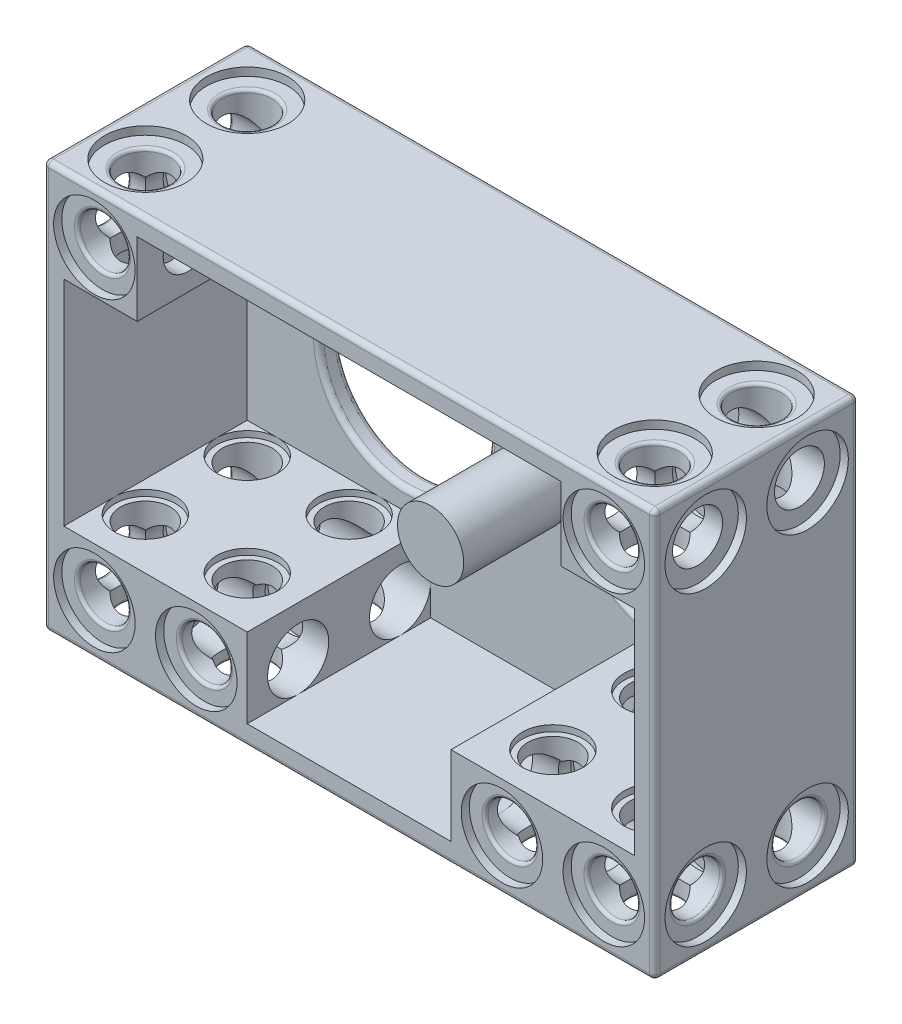
SolidWorks part; units mm, degrees
ref_plane "Front Plane" through (0, 0, 0) normal (0, 0, 1) x (1, 0, 0)
ref_plane "Top Plane" through (0, 0, 0) normal (0, 1, 0) x (1, 0, 0)
ref_plane "Right Plane" through (0, 0, 0) normal (1, 0, 0) x (0, 0, -1)
sketch "Sketch1" plane through (0, 0, 0) normal (0, 0, 1) x (1, 0, 0)
  line L0 (0, 20) -> (0, -20) construction
  line L1 (-30, -20) -> (30, -20)
  line L2 (-30, -20) -> (-30, 20)
  line L3 (-30, 20) -> (30, 20)
  line L4 (30, -20) -> (30, 20)
  line L5 (-30, -20) -> (30, 20) construction
  line L6 (-30, 20) -> (30, -20) construction
  line L7 (-23, 10.8) -> (23, 10.8)
  line L8 (-23, 10.8) -> (-23, -10.2)
  line L9 (-23, -10.2) -> (23, -10.2)
  line L10 (23, 10.8) -> (23, -10.2)
  line L11 (-12.6, 0.2) -> (12.6, 0.2) construction
  line L12 (-30, 12.5) -> (30, 12.5) construction
  line L13 (-30, -12.5) -> (30, -12.5) construction
  line L14 (30, -12.5) -> (35.4967, -17.0033) construction
  line L15 (-30, -2.5) -> (30, -2.5) construction
  line L16 (-20, 20) -> (-20, -20) construction
  line L17 (20, 20) -> (20, -20) construction
  line L18 (-30, 2.5) -> (30, 2.5) construction
  circle A0 centre (-12.6, 0.2) radius 8.4
  circle A1 centre (12.6, 0.2) radius 8.4
  point P0 (0, 0)
  point P12 (0, -10.2)
  point P17 (0, 0.2)
  point P31 (0, 0)
  dimension "D5" = 16.8
  dimension "D1" = 40
  dimension "D2" = 60
  dimension "D3" = 46
  dimension "D4" = 21
  dimension "D6" = 25.2
  dimension "D7" = 10.6
  dimension "D8" = 7.5
  dimension "D9" = 7.5
  dimension "D10" = 10
  dimension "D11" = 10
  dimension "D12" = 10
  dimension "D13" = 10
  dimension "D14" = 9.2
extrude "Boss-Extrude1" add sketch "Sketch1" along normal blind 2 contours L1 L4 L3 L2 L7 L10 L9 L8 | L10 L7 L8 L9 A1 A0
sketch "Sketch2" plane through (0, 0, 2) normal (0, 0, 1) x (1, 0, 0)
  line L0 (0, 20) -> (0, -20) construction
  line L1 (-23, 10.8) -> (23, 10.8) construction
  circle A0 centre (0, -1.7) radius 3.25
  dimension "D1" = 6.5
  dimension "D2" = 12.5
extrude "Boss-Extrude2" add sketch "Sketch2" along normal blind 10
sketch "Sketch3" plane through (0, 0, 2) normal (0, 0, 1) x (1, 0, 0)
  line L0 (-30, -20) -> (30, -20) construction
  line L1 (30, -20) -> (30, 20) construction
  line L2 (-30, 20) -> (30, 20) construction
  line L3 (-30, -20) -> (-30, 20) construction
  line L4 (-30, -20) -> (30, -20)
  line L5 (30, -20) -> (30, 20)
  line L6 (-30, 20) -> (30, 20)
  line L7 (-30, -20) -> (-30, 20)
  line L8 (-28, -18) -> (28, -18)
  line L9 (28, -18) -> (28, 18)
  line L10 (-28, 18) -> (28, 18)
  line L11 (-28, -18) -> (-28, 18)
  dimension "D1" = 2
extrude "Boss-Extrude4" add sketch "Sketch3" along normal offset from surface (18 mm away) 20 up to face at (0, 0, 0)
sketch "Sketch5" plane through (0, 0, 2) normal (0, 0, 1) x (1, 0, 0)
  line L0 (-23, 10.8) -> (23, 10.8) construction
  line L1 (-30, 20) -> (-20.8, 20)
  line L2 (-30, 20) -> (-30, 10.8)
  line L3 (-30, 10.8) -> (-20.8, 10.8)
  line L4 (-20.8, 20) -> (-20.8, 10.8)
  line L6 (30, 20) -> (20.8, 20)
  line L7 (30, 20) -> (30, 10.8)
  line L8 (30, 10.8) -> (20.8, 10.8)
  line L9 (20.8, 20) -> (20.8, 10.8)
  line L11 (30, -20) -> (20.8, -20)
  line L12 (30, -20) -> (30, -10.2)
  line L13 (30, -10.2) -> (20.8, -10.2)
  line L14 (20.8, -20) -> (20.8, -10.2)
  line L15 (-30, -20) -> (-20.8, -20)
  line L16 (-30, -20) -> (-30, -10.2)
  line L17 (-30, -10.2) -> (-20.8, -10.2)
  line L18 (-20.8, -20) -> (-20.8, -10.2)
  line L19 (-23, -10.2) -> (23, -10.2) construction
  point P23 (0, 0)
  point P24 (0, 0)
  dimension "D1" = 9.2
extrude "Boss-Extrude5" add sketch "Sketch5" along normal up to surface (18 mm away) up to face at (0, 0, 20)
sketch "Sketch7" plane through (0, 0, 2) normal (0, 0, 1) x (1, 0, 0)
  line L1 (-30, 20) -> (-21, 20)
  line L2 (-30, 20) -> (-30, 10.8)
  line L3 (-30, 10.8) -> (-21, 10.8)
  line L4 (-21, 20) -> (-21, 10.8)
  line L5 (30, 20) -> (21, 20)
  line L6 (30, 20) -> (30, 10.8)
  line L7 (30, 10.8) -> (21, 10.8)
  line L8 (21, 20) -> (21, 10.8)
  dimension "D1" = 9
  dimension "D2" = 9.2
  dimension "D3" = 9.2
  dimension "D4" = 9
extrude "Boss-Extrude6" add sketch "Sketch7" along normal up to surface (18 mm away)
sketch "Sketch8" plane through (0, 0, 2) normal (0, 0, 1) x (1, 0, 0)
  line L0 (30, -20) -> (30, 20) construction
  line L1 (-30, -20) -> (30, -20)
  line L2 (-30, -20) -> (-30, -10.2)
  line L3 (-30, -10.2) -> (30, -10.2)
  line L4 (30, -20) -> (30, -10.2)
  line L5 (0, 20) -> (0, -20) construction
  line L6 (-6, -20) -> (6, -20)
  line L7 (-6, -20) -> (-6, -10.2)
  line L8 (-6, -10.2) -> (6, -10.2)
  line L9 (6, -20) -> (6, -10.2)
  line L10 (-20.8, -10.2) -> (-28, -10.2) construction
  line L11 (-30, -20) -> (-10, -20)
  line L12 (-30, -20) -> (-30, -10.2)
  line L13 (-30, -10.2) -> (-10, -10.2)
  line L14 (-10, -20) -> (-10, -10.2)
  line L15 (30, -20) -> (10, -20)
  line L16 (30, -20) -> (30, -10.2)
  line L17 (30, -10.2) -> (10, -10.2)
  line L18 (10, -20) -> (10, -10.2)
  point P19 (0, 0)
  line M24 (-20.8, -10.2) -> (-20.8, -18)
  line M25 (-20.8, -18) -> (20.8, -18)
  line M26 (20.8, -18) -> (20.8, -10.2)
  dimension "D2" = 12
  dimension "D3" = 6
  dimension "D4" = 20
  dimension "D5" = 20
extrude "Boss-Extrude7" add sketch "Sketch8" along normal up to surface (18 mm away) contours L14 L3 M25 M24 | L18 L3 M25 M26
sketch "Sketch9" plane through (-30, 0, 0) normal (-1, 0, 0) x (0, 0, 1)
  line L0 (0, 15) -> (20, 15) construction
  line L1 (0, -20) -> (0, 20) construction
  line L2 (20, 20) -> (20, -20) construction
  line L3 (20, 20) -> (0, 20) construction
  line L4 (0, 0) -> (20, 0) construction
  circle A0 centre (5, 15) radius 2.45
  circle A1 centre (15, 15) radius 2.45
  circle A2 centre (5, -15) radius 2.45
  circle A3 centre (15, -15) radius 2.45
  dimension "D1" = 5
  dimension "D2" = 4.9
  dimension "D3" = 5
  dimension "D4" = 10
extrude "Cut-Extrude1" cut sketch "Sketch9" against normal through all
sketch "Sketch10" plane through (0, 20, 0) normal (0, 1, 0) x (1, 0, 0)
  line L0 (-25, 0) -> (-25, -20) construction
  line L1 (-30, 0) -> (30, 0) construction
  line L2 (30, -20) -> (-30, -20) construction
  line L3 (-30, -20) -> (-30, 0) construction
  line L4 (0, 0) -> (0, -20) construction
  circle A0 centre (-25, -5) radius 2.45
  circle A1 centre (-25, -15) radius 2.45
  circle A2 centre (25, -15) radius 2.45
  circle A3 centre (25, -5) radius 2.45
  dimension "D1" = 5
  dimension "D2" = 4.9
  dimension "D3" = 5
  dimension "D4" = 10
extrude "Cut-Extrude2" cut sketch "Sketch10" against normal through all
sketch "Sketch11" plane through (0, -20, 0) normal (0, -1, 0) x (1, 0, 0)
  line L0 (-15, 20) -> (-15, 0) construction
  line L1 (-30, 20) -> (30, 20) construction
  line L2 (-30, 0) -> (30, 0) construction
  line L3 (0, 0) -> (0, 20) construction
  circle A0 centre (-15, 15) radius 2.45
  circle A1 centre (-15, 5) radius 2.45
  circle A2 centre (-25, 15) radius 2.45 construction
  circle A3 centre (15, 15) radius 2.45
  circle A4 centre (15, 5) radius 2.45
  dimension "D1" = 10
  dimension "D2" = 4.9
  dimension "D3" = 5
  dimension "D4" = 10
extrude "Cut-Extrude3" cut sketch "Sketch11" against normal blind 13
sketch "Sketch12" plane through (0, 0, 20) normal (0, 0, 1) x (1, 0, 0)
  line L0 (-30, -15) -> (30, -15) construction
  line L1 (-30, 20) -> (-30, -20) construction
  line L2 (30, -20) -> (30, 20) construction
  line L3 (0, 0) -> (18.5352, 0) construction
  line L4 (0, -20) -> (0, 0) construction
  line L5 (-30, -20) -> (30, -20) construction
  circle A0 centre (-25, -15) radius 2.45
  circle A1 centre (-15, -15) radius 2.45
  circle A2 centre (15, -15) radius 2.45
  circle A3 centre (25, -15) radius 2.45
  circle A4 centre (25, 15) radius 2.45
  circle A5 centre (-25, 15) radius 2.45
  dimension "D1" = 5
  dimension "D2" = 4.9
  dimension "D3" = 5
  dimension "D4" = 10
extrude "Cut-Extrude4" cut sketch "Sketch12" against normal blind 10
sketch "Sketch13" plane through (0, 20, 0) normal (0, 1, 0) x (1, 0, 0)
  circle A0 centre (-25, -5) radius 4
  circle A1 centre (-25, -15) radius 4
  circle A2 centre (25, -5) radius 4
  circle A3 centre (25, -15) radius 4
  dimension "D1" = 8
extrude "Cut-Extrude5" cut sketch "Sketch13" against normal blind 0.8
sketch "Sketch14" plane through (30, 0, 0) normal (1, 0, 0) x (0, 0, -1)
  circle A0 centre (-15, 15) radius 4
  circle A1 centre (-5, 15) radius 4
  circle A2 centre (-15, -15) radius 4
  circle A3 centre (-5, -15) radius 4
  dimension "D1" = 8
extrude "Cut-Extrude6" cut sketch "Sketch14" against normal blind 0.8
mirror "Mirror1" about plane through (0, 0, 0) normal (0, 1, 0) of "Cut-Extrude5"
mirror "Mirror2" about plane through (0, 0, 0) normal (1, 0, 0) of "Cut-Extrude6"
sketch "Sketch15" plane through (0, -10.2, 0) normal (0, 1, 0) x (1, 0, 0)
  line L0 (28, -2) -> (10, -2) construction
  circle A0 centre (-25, -5) radius 3
  circle A1 centre (-25, -15) radius 3
  circle A2 centre (25, -5) radius 3
  circle A3 centre (25, -15) radius 3
  circle A5 centre (-15, -5) radius 3
  circle A6 centre (-15, -15) radius 3
  circle A7 centre (15, -15) radius 3
  circle A8 centre (15, -5) radius 3
extrude "Cut-Extrude7" cut sketch "Sketch15" against normal offset from surface (0.6 mm away) 8.4 up to face at (-25, -19.2, 19)
sketch "Sketch16" plane through (0, -20, 0) normal (0, -1, 0) x (1, 0, 0)
  circle A0 centre (-15, 15) radius 4
  circle A1 centre (-15, 5) radius 4
  circle A2 centre (15, 5) radius 4
  circle A3 centre (15, 15) radius 4
  circle A4 centre (-25, 15) radius 4 construction
extrude "Cut-Extrude8" cut sketch "Sketch16" against normal blind 0.8
sketch "Sketch17" plane through (-20.8, 0, 0) normal (1, 0, 0) x (0, 0, -1)
  circle A0 centre (-15, -15) radius 3
  circle A1 centre (-5, -15) radius 3
  dimension "D1" = 6
extrude "Cut-Extrude9" cut sketch "Sketch17" along normal up to surface (41.6 mm away) up to face at (20.8, 17.45, 15)
sketch "Sketch18" plane through (0, 0, 20) normal (0, 0, 1) x (1, 0, 0)
  circle A0 centre (-25, 15) radius 4
  circle A1 centre (25, 15) radius 4
  circle A2 centre (25, -15) radius 4
  circle A3 centre (15, -15) radius 4
  circle A4 centre (-15, -15) radius 4
  circle A5 centre (-25, -15) radius 4
  dimension "D1" = 8
extrude "Cut-Extrude11" cut sketch "Sketch18" against normal blind 0.8
ref_plane "Plane1" through (0, 0, 10.8) normal (0, 0, 1) x (1, 0, 0)
sketch "Sketch19" plane through (0, 0, 10.8) normal (0, 0, 1) x (1, 0, 0)
  circle A0 centre (-15, -15) radius 3
  circle A1 centre (-25, -15) radius 3
  circle A2 centre (15, -15) radius 3
  circle A3 centre (25, -15) radius 3
  circle A4 centre (25, 15) radius 3
  circle A5 centre (-25, 15) radius 3
  dimension "D1" = 6
extrude "Cut-Extrude12" cut sketch "Sketch19" against normal blind 0.8
fillet "Fillet1" radius 0.3 24 edges at (-15, -19.2, 12.55) (-15, -19.2, 2.55) (-25, -19.2, 2.55) (-25, -19.2, 12.55) (15, -19.2, 2.55) (25, -19.2, 2.55) (25, -19.2, 12.55) (15, -19.2, 12.55) (29.2, -15, 2.55) (29.2, -15, 12.55) (-29.2, -15, 17.45) (-29.2, -15, 7.45) (-29.2, 15, 17.45) (-29.2, 15, 7.45) (25, 19.2, 7.45) (-25, 19.2, 7.45) (-25, 19.2, 17.45) (25, 19.2, 17.45) (27.45, 15, 19.2) (27.45, -15, 19.2) (17.45, -15, 19.2) (-12.55, -15, 19.2) (-22.55, -15, 19.2) (-22.55, 15, 19.2)
fillet "Fillet2" radius 0.5 12 edges at (0, -20, 0) (0, -20, 20) (30, 0, 20) (30, 0, 0) (30, 20, 10) (0, 20, 0) (0, 20, 20) (-30, 0, 20) (-30, 0, 0) (-30, -20, 10) (-30, 20, 10) (30, -20, 10)
fillet "Fillet3" radius 0.5 4 edges at (21, 0.2, 2) (-4.2, 0.2, 2) (-4.2, 0.2, 0) (21, 0.2, 0)
